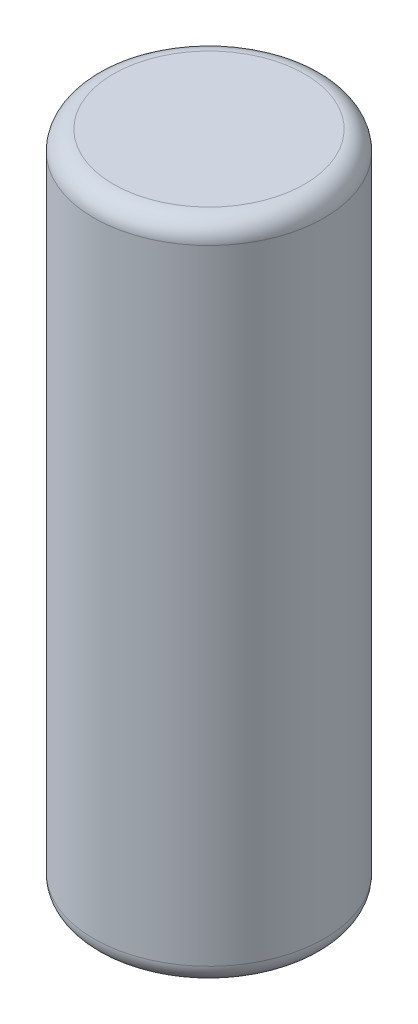
SolidWorks part; units mm, degrees
ref_plane "Front Plane" through (0, 0, 0) normal (0, 0, 1) x (1, 0, 0)
ref_plane "Top Plane" through (0, 0, 0) normal (0, 1, 0) x (1, 0, 0)
ref_plane "Right Plane" through (0, 0, 0) normal (1, 0, 0) x (0, 0, -1)
sketch "Sketch1" plane through (0, 0, 0) normal (0, 1, 0) x (1, 0, 0)
  circle A0 centre (0, 0) radius 2.95
extrude "Boss-Extrude1" add sketch "Sketch1" along normal blind 17
fillet "Fillet1" radius 0.5 2 edges at (0, 0, 2.95) (0, 17, 2.95)
